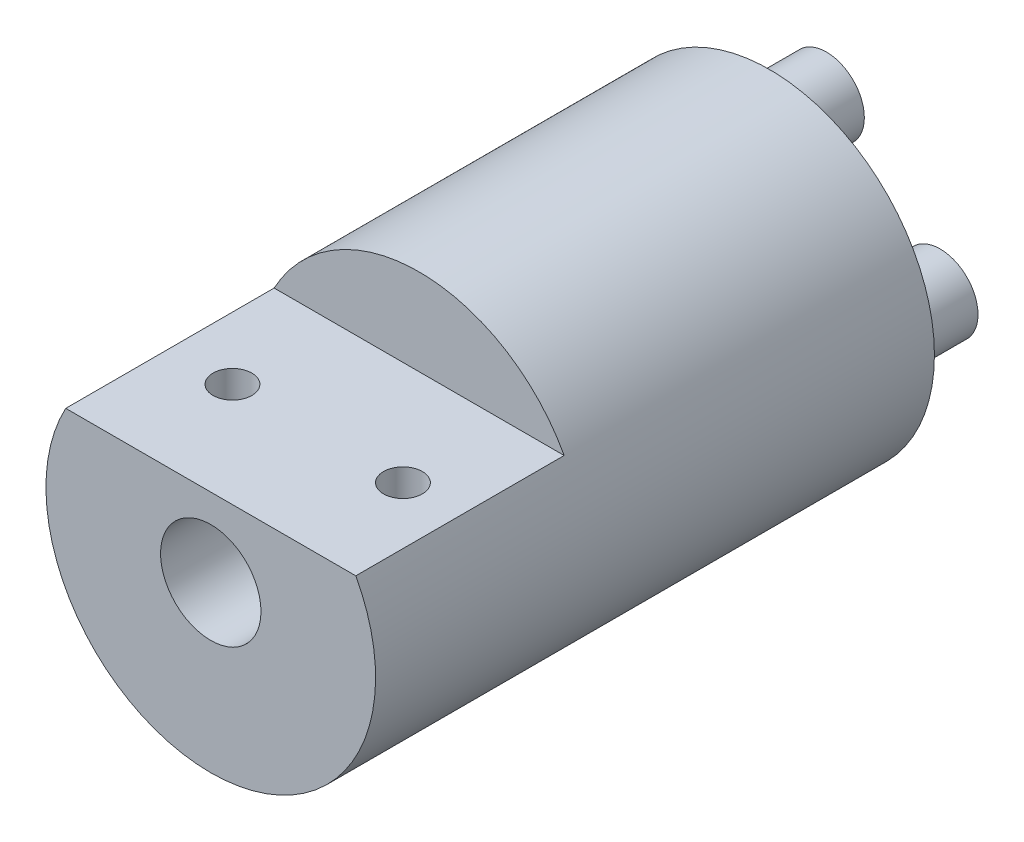
SolidWorks part; units mm, degrees
ref_plane "Front Plane" through (0, 0, 0) normal (0, 0, 1) x (1, 0, 0)
ref_plane "Top Plane" through (0, 0, 0) normal (0, 1, 0) x (1, 0, 0)
ref_plane "Right Plane" through (0, 0, 0) normal (1, 0, 0) x (0, 0, -1)
sketch "Sketch1" plane through (0, 0, 0) normal (0, 0, 1) x (1, 0, 0)
  circle A0 centre (0, 0) radius 8.7
  dimension "D1" = 17.4
extrude "Boss-Extrude1" add sketch "Sketch1" along normal blind 29.5 contours A0
sketch "Sketch2" plane through (0, 0, 29.5) normal (0, 0, 1) x (1, 0, 0)
  line L1 (-7.6555, 8.7) -> (9.3445, 8.7)
  line L2 (-7.6555, 8.7) -> (-7.6555, 4.1331)
  line L3 (-7.6555, 4.1331) -> (9.3445, 4.1331)
  line L4 (9.3445, 8.7) -> (9.3445, 4.1331)
  circle A0 centre (0, 0) radius 8.7 construction
  dimension "D1" = 17
sketch "Sketch4" plane through (0, 0, 0) normal (0, 0, -1) x (-1, 0, 0)
  circle A0 centre (0, 6) radius 2
  circle A1 centre (6, 0) radius 2
  circle A2 centre (0, -6) radius 2
  circle A3 centre (-6, 0) radius 2
  dimension "D1" = 4
  dimension "D2" = 6
  dimension "D3" = 6
  dimension "D4" = 6
  dimension "D5" = 6
sketch "Sketch5" plane through (0, 0, 0) normal (0, 0, -1) x (-1, 0, 0)
  circle A0 centre (0, 0) radius 1.75
  dimension "D1" = 3.5
extrude "Cut-Extrude1" cut sketch "Sketch5" against normal through all
sketch "Sketch6" plane through (0, 0, 29.5) normal (0, 0, 1) x (1, 0, 0)
  circle A0 centre (0, 0) radius 2.65
  dimension "D1" = 5.3
extrude "Cut-Extrude3" cut sketch "Sketch6" against normal blind 20.9
extrude "Cut-Extrude4" cut sketch "Sketch2" against normal blind 11 contours L1 L4 L3 L2
fillet "Fillet1" radius 0.3 1 edges at (1.75, 0, 8.6)
hole_wizard "Tap Drill for M2.5x0.45 Tap1" positions "Sketch7" profile "Sketch8" hole size "M2.5x0.45" standard "ANSI Metric" end condition through all
sketch "Sketch7" plane through (0, 4.1331, 0) normal (0, 1, 0) x (1, 0, 0)
  line L0 (-7.6555, -29.5) -> (7.6555, -29.5) construction
  line L1 (-7.6555, -18.5) -> (-7.6555, -29.5) construction
  point P0 (4.6445, -24)
  point P2 (-4.3555, -24)
  dimension "D1" = 9
  dimension "D2" = 5.5
  dimension "D3" = 3.3
sketch "Sketch8" plane through (4.6445, 4.1331, 24) normal (1, 0, 0) x (0, 0, 1)
  line L0 (0, 0) -> (0, 12.8331)
  line L1 (0, 12.8331) -> (1.025, 12.8331)
  line L2 (1.025, 12.8331) -> (1.025, 0)
  line L5 (1.025, 0) -> (0, 0)
  line L11 (0, -6.35) -> (0, 107.95) construction
  dimension "Thru Hole Dia." = 2.05
  dimension "Thru Hole Depth" = 12.8331
extrude "Boss-Extrude2" add sketch "Sketch4" along normal blind 3
